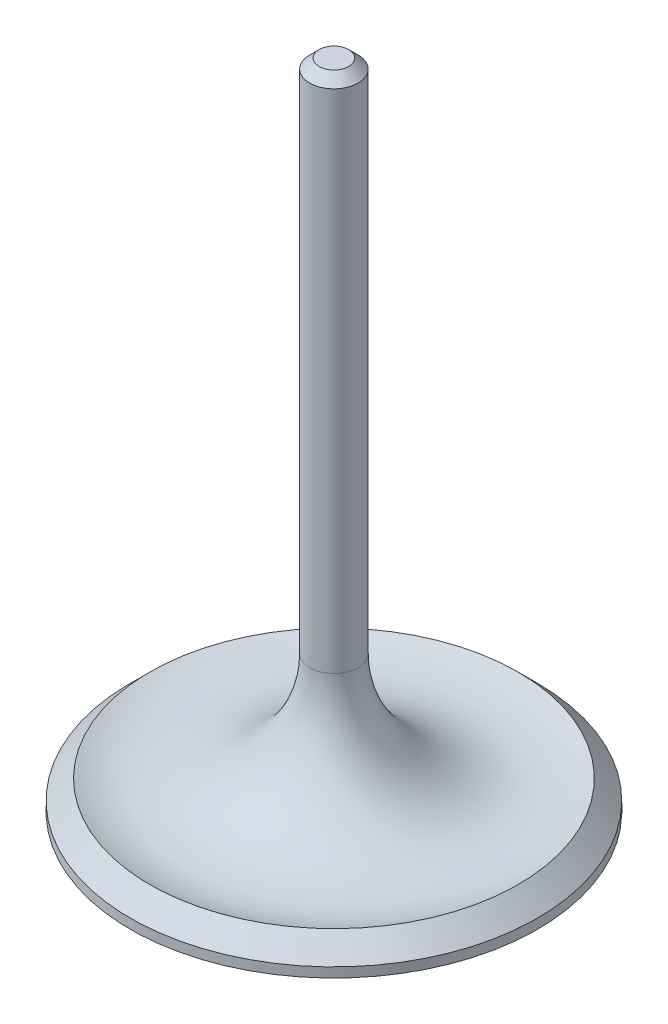
SolidWorks part; units mm, degrees
ref_plane "Front Plane" through (0, 0, 0) normal (0, 0, 1) x (1, 0, 0)
ref_plane "Top Plane" through (0, 0, 0) normal (0, 1, 0) x (1, 0, 0)
ref_plane "Right Plane" through (0, 0, 0) normal (1, 0, 0) x (0, 0, -1)
sketch "Sketch2" plane through (0, 0, 0) normal (1, 0, 0) x (0, 0, -1)
  line L0 (0, 0) -> (0, 85.55)
  line L1 (3.18, 85.55) -> (3.18, 17.9547)
  line L2 (0, 85.55) -> (3.18, 85.55)
  line L3 (24.13, 3.81) -> (26.67, 1.27)
  line L4 (26.67, 1.27) -> (26.67, 0)
  line L5 (26.67, 0) -> (0, 0)
  arc A1 (3.18, 17.9547) -> (24.13, 3.81) centre (18.43, 17.9547) ccw
  dimension "D7" = 15.25
  dimension "D1" = 85.55
  dimension "D2" = 26.67
  dimension "D3" = 1.27
  dimension "D4" = 3.81
  dimension "D5" = 45
  dimension "D6" = 3.18
revolve "Revolve1" add sketch "Sketch2" angle 360 about L0
chamfer "Chamfer1" distance 1.25 angle 45 1 edges at (0, 85.55, -3.18)
